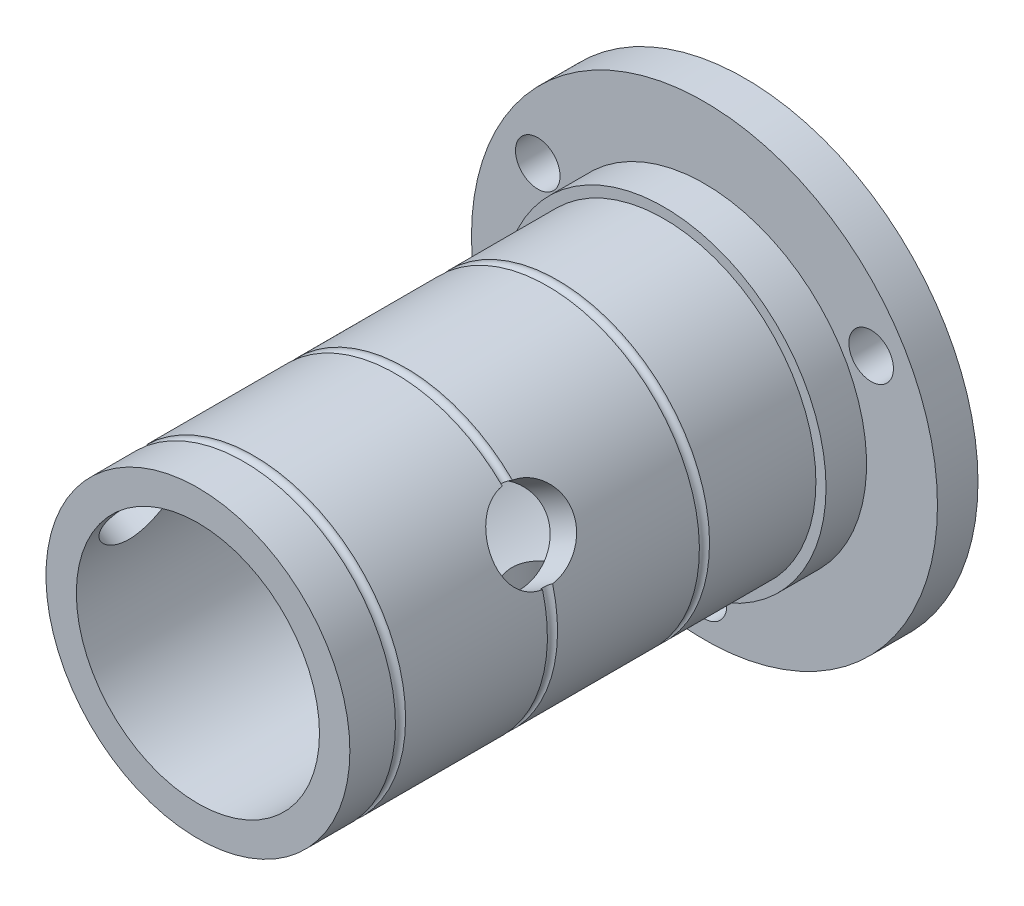
SolidWorks part; units mm, degrees
ref_plane "前视基准面" through (0, 0, 0) normal (0, 0, 1) x (1, 0, 0)
ref_plane "上视基准面" through (0, 0, 0) normal (0, 1, 0) x (1, 0, 0)
ref_plane "右视基准面" through (0, 0, 0) normal (1, 0, 0) x (0, 0, -1)
other "Configuration Table"
sketch "草图1" plane through (0, 0, 0) normal (0, 0, 1) x (1, 0, 0)
  circle A0 centre (0, 0) radius 15
  circle A1 centre (0, 0) radius 12
  dimension "D1" = 30
  dimension "D2" = 24
extrude "凸台-拉伸1" add sketch "草图1" along normal blind 50
sketch "草图2" plane through (0, 0, 0) normal (0, 0, -1) x (-1, 0, 0)
  line L0 (-6.0622, 35.5) -> (-33.775, -12.5) construction
  line L1 (0, 30) -> (-25.9808, -15) construction
  line L2 (-25.9808, -15) -> (25.9808, -15) construction
  line L3 (25.9808, -15) -> (0, 30) construction
  line L4 (-27.7128, -23) -> (27.7128, -23) construction
  line L5 (33.775, -12.5) -> (6.0622, 35.5) construction
  line L6 (-39.8372, -23) -> (39.8372, -23) construction
  line L7 (0, 46) -> (-39.8372, -23) construction
  line L8 (39.8372, -23) -> (0, 46) construction
  line L9 (0, 0) -> (0, -23) construction
  circle A0 centre (0, 0) radius 15 construction
  circle A1 centre (0, 30) radius 2.75 construction
  circle A2 centre (25.9808, -15) radius 2.75 construction
  circle A3 centre (-25.9808, -15) radius 2.75 construction
  arc A4 (-27.7128, -23) -> (-33.775, -12.5) centre (-27.7128, -16) cw construction
  arc A5 (27.7128, -23) -> (33.775, -12.5) centre (27.7128, -16) ccw construction
  arc A6 (6.0622, 35.5) -> (-6.0622, 35.5) centre (0, 32) ccw construction
  circle A7 centre (0, 0) radius 23
  circle A8 centre (0, -19) radius 2.2
  circle A9 centre (-16.4545, 9.5) radius 2.2
  circle A10 centre (16.4545, 9.5) radius 2.2
  point P13 (0, 0)
  point P34 (0, 0)
  dimension "D2" = 5.5
  dimension "D5" = 7
  dimension "D6" = 4.4
  dimension "D1" = 30
  dimension "D7" = 19
  dimension "D4" = 8
  dimension "D3" = 3
  dimension "D8" = 3
extrude "凸台-拉伸2" add sketch "草图2" along normal blind 4
sketch "草图3" plane through (0, 0, 0) normal (0, 0, 1) x (1, 0, 0)
  circle A0 centre (0, 0) radius 16
  dimension "D1" = 32
extrude "凸台-拉伸3" add sketch "草图3" along normal blind 4
sketch "草图4" plane through (0, 0, 4) normal (0, 0, 1) x (1, 0, 0)
  circle A1 centre (0, 0) radius 12
  circle A2 centre (0, 0) radius 12
  dimension "D1" = 0
extrude "切除-拉伸1" cut sketch "草图4" against normal through all
sketch "草图5" plane through (0, 0, 0) normal (0, 1, 0) x (1, 0, 0)
  line L0 (-15, -4) -> (15, -4) construction
  line L1 (0, 0) -> (0, -50) construction
  line L2 (-15, -50) -> (15, -50) construction
  circle A0 centre (0, -15) radius 4
  dimension "D1" = 8
  dimension "D2" = 11
extrude "切除-拉伸2" cut sketch "草图5" against normal through all
ref_plane "基准面1" through (0, 0, 0) normal (-0.866, -0.5, 0) x (0, 0, 1)
sketch "草图6" plane through (0, 0, 0) normal (-0.866, -0.5, 0) x (0, 0, 1)
  line L0 (0, 0) -> (50, 0) construction
  line L1 (0, 0) -> (50, 0) construction
  line L2 (4, -16) -> (4, 16) construction
  circle A0 centre (30, 0) radius 4
  dimension "D1" = 8
  dimension "D2" = 26
extrude "切除-拉伸3" cut sketch "草图6" against normal through all
ref_plane "基准面2" through (0, 0, 0) normal (0.866, -0.5, 0) x (0, 0, 1)
sketch "草图7" plane through (0, 0, 0) normal (0.866, -0.5, 0) x (0, 0, 1)
  line L0 (0, 0) -> (50, 0) construction
  line L1 (0, 0) -> (50, 0) construction
  line L2 (4, -16) -> (4, 16) construction
  circle A0 centre (45, 0) radius 4
  dimension "D1" = 8
  dimension "D2" = 41
extrude "切除-拉伸4" cut sketch "草图7" against normal through all
sketch "草图8" plane through (0, 0, 0) normal (0, 1, 0) x (1, 0, 0)
  line L0 (0, 4) -> (0, -50) construction
  line L1 (12, 4) -> (-12, 4) construction
  line L2 (-15, -50) -> (15, -50) construction
  line L3 (-15, -4) -> (-15, -50) construction
  line L4 (-15, -4) -> (15, -4) construction
  circle A0 centre (-15, -15) radius 0.5
  circle A1 centre (-15, -30) radius 0.5
  circle A2 centre (-15, -45) radius 0.5
  dimension "D1" = 1
  dimension "D2" = 11
  dimension "D4" = 15
  dimension "D3" = 3
revolve "切除-旋转1" cut sketch "草图8" angle 360 about L0
